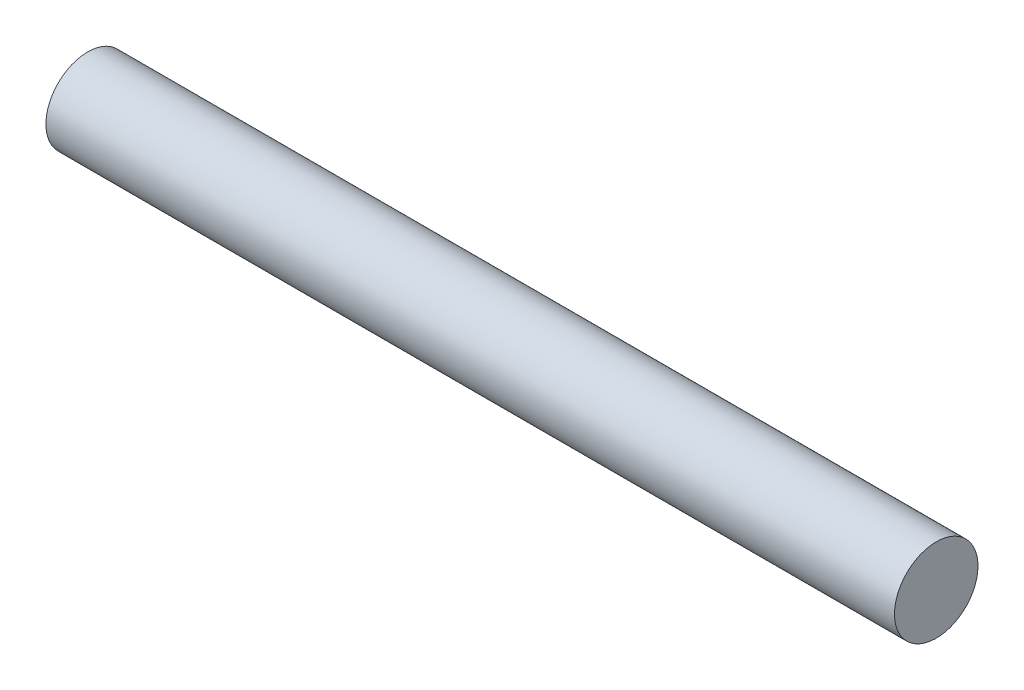
SolidWorks part; units mm, degrees
ref_plane "Front Plane" through (0, 0, 0) normal (0, 0, 1) x (1, 0, 0)
ref_plane "Top Plane" through (0, 0, 0) normal (0, 1, 0) x (1, 0, 0)
ref_plane "Right Plane" through (0, 0, 0) normal (1, 0, 0) x (0, 0, -1)
sketch "Sketch1" plane through (0, 0, 0) normal (1, 0, 0) x (0, 0, -1)
  circle A0 centre (0, 0) radius 2.5
  dimension "D1" = 5
extrude "Boss-Extrude1" add sketch "Sketch1" along normal blind 50.8
